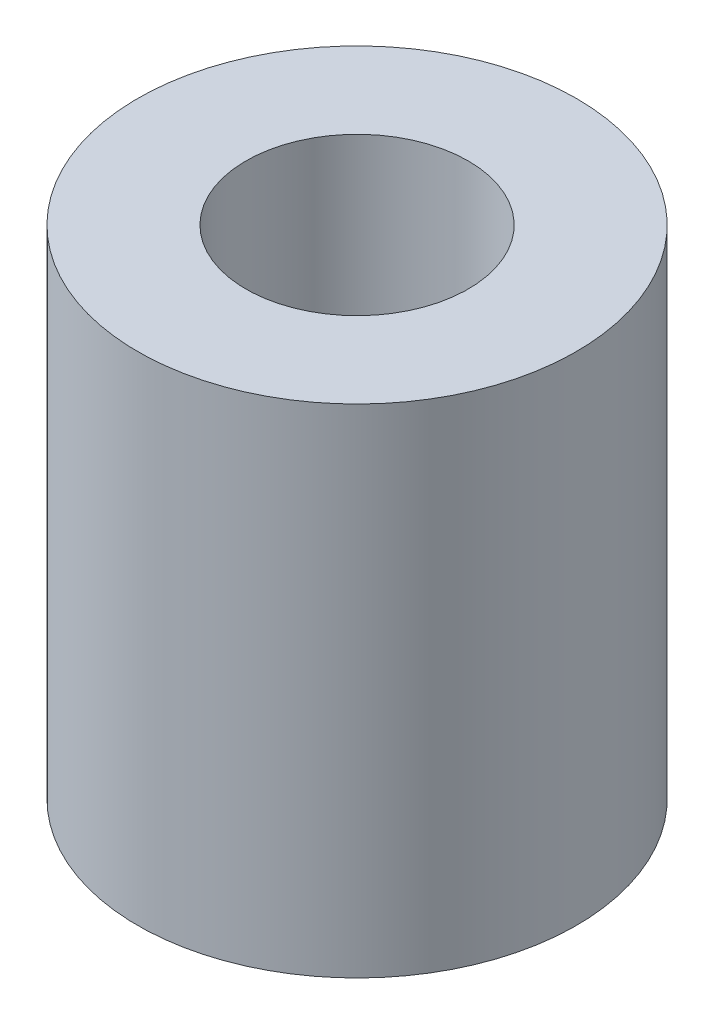
SolidWorks part; units mm, degrees
material "Nylon 101"
ref_plane "Front Plane" through (0, 0, 0) normal (0, 0, 1) x (1, 0, 0)
ref_plane "Top Plane" through (0, 0, 0) normal (0, 1, 0) x (1, 0, 0)
ref_plane "Right Plane" through (0, 0, 0) normal (1, 0, 0) x (0, 0, -1)
ref_plane "Plane1" through (0, 21.59, 0) normal (0, 1, 0) x (1, 0, 0)
sketch "Sketch1" plane through (0, 21.59, 0) normal (0, 1, 0) x (1, 0, 0)
  circle A0 centre (0, 0) radius 4.826
  circle A1 centre (0, 0) radius 9.525
extrude "Boss-Extrude1" add sketch "Sketch1" against normal blind 21.59
